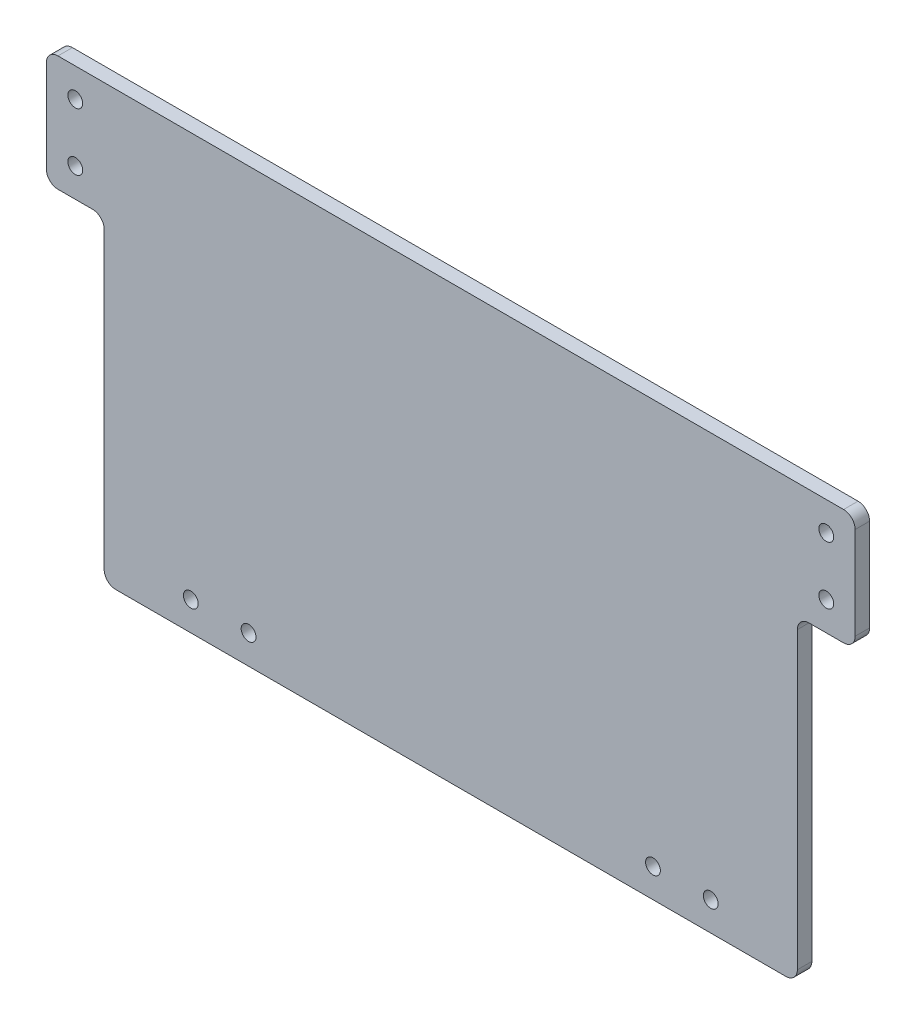
SolidWorks part; units mm, degrees
ref_plane "Front Plane" through (0, 0, 0) normal (0, 0, 1) x (1, 0, 0)
ref_plane "Top Plane" through (0, 0, 0) normal (0, 1, 0) x (1, 0, 0)
ref_plane "Right Plane" through (0, 0, 0) normal (1, 0, 0) x (0, 0, -1)
sketch "Sketch1" plane through (0, 0, 0) normal (0, 0, 1) x (1, 0, 0)
  line L1 (-152.4, 95.25) -> (152.4, 95.25)
  line L2 (-152.4, 95.25) -> (-152.4, -95.25)
  line L3 (-152.4, -95.25) -> (152.4, -95.25)
  line L4 (152.4, 95.25) -> (152.4, -95.25)
  line L5 (-152.4, 95.25) -> (152.4, -95.25) construction
  line L6 (-152.4, -95.25) -> (152.4, 95.25) construction
  point P0 (0, 0)
  dimension "D1" = 304.8
  dimension "D2" = 190.5
extrude "Boss-Extrude1" add sketch "Sketch1" along normal blind 6.35
sketch "Sketch2" plane through (0, 0, 6.35) normal (0, 0, 1) x (1, 0, 0)
  line L0 (-114.3, -82.55) -> (-88.9, -82.55) construction
  line L1 (-88.9, -82.55) -> (88.9, -82.55) construction
  line L2 (88.9, -82.55) -> (114.3, -82.55) construction
  line L3 (-152.4, -95.25) -> (152.4, -95.25) construction
  circle A0 centre (-114.3, -82.55) radius 3.2639
  circle A1 centre (-88.9, -82.55) radius 3.2639
  circle A2 centre (88.9, -82.55) radius 3.2639
  circle A3 centre (114.3, -82.55) radius 3.2639
  point P11 (0, -82.55)
  dimension "D1" = 6.5278
  dimension "D2" = 25.4
  dimension "D3" = 12.7
  dimension "D4" = 177.8
extrude "Cut-Extrude1" cut sketch "Sketch2" against normal through all
sketch "Sketch3" plane through (0, 0, 0) normal (0, 0, 1) x (1, 0, 0)
  line L0 (-165.1, 82.55) -> (-165.1, 57.15) construction
  line L1 (-152.4, 95.25) -> (-177.8, 95.25)
  line L2 (-152.4, 95.25) -> (-152.4, 44.45)
  line L3 (-152.4, 44.45) -> (-177.8, 44.45)
  line L4 (-177.8, 95.25) -> (-177.8, 44.45)
  circle A0 centre (-165.1, 82.55) radius 3.2639
  circle A1 centre (-165.1, 57.15) radius 3.2639
  dimension "D1" = 6.5278
  dimension "D2" = 25.4
  dimension "D3" = 12.7
  dimension "D4" = 12.7
  dimension "D5" = 25.4
  dimension "D6" = 12.7
extrude "Boss-Extrude2" add sketch "Sketch3" along normal up to surface (6.35 mm away) up to face at (-85.6361, -82.55, 6.35)
mirror "Mirror1" about plane through (0, 0, 0) normal (1, 0, 0) of "Boss-Extrude2"
sketch "Sketch4" [suppressed] plane through (0, 0, 6.35) normal (0, 0, 1) x (1, 0, 0)
  line L0 (-152.4, 44.45) -> (-152.4, -95.25) construction
  line L1 (-63.5, -31.75) -> (-45.72, -31.75)
  line L2 (-63.5, -31.75) -> (-63.5, -42.418)
  line L3 (-63.5, -42.418) -> (-45.72, -42.418)
  line L4 (-45.72, -31.75) -> (-45.72, -42.418)
  line L5 (-63.5, -31.75) -> (-45.72, -42.418) construction
  line L6 (-63.5, -42.418) -> (-45.72, -31.75) construction
  line L7 (177.8, 95.25) -> (-177.8, 95.25) construction
  point P0 (-54.61, -37.084)
  dimension "D1" = 10.668
  dimension "D2" = 17.78
  dimension "D3" = 88.9
  dimension "D4" = 127
extrude "Cut-Extrude2" [suppressed] cut sketch "Sketch4" against normal through all
fillet "Fillet1" radius 5.08 8 edges at (-177.8, 44.45, 3.175) (-152.4, 44.45, 3.175) (-152.4, -95.25, 3.175) (152.4, -95.25, 3.175) (152.4, 44.45, 3.175) (177.8, 44.45, 3.175) (177.8, 95.25, 3.175) (-177.8, 95.25, 3.175)
